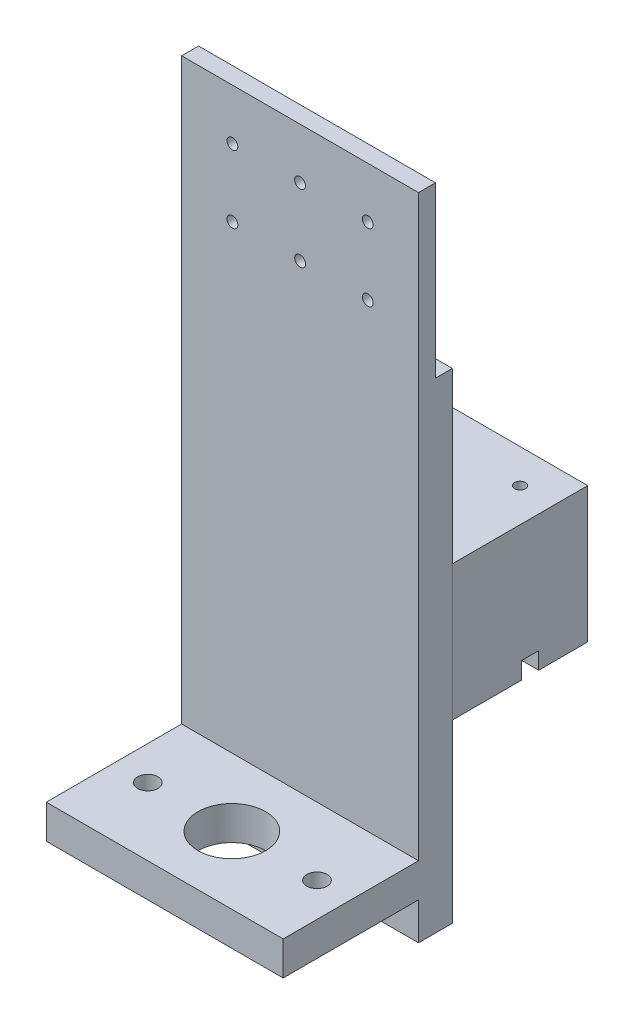
SolidWorks part; units mm, degrees
ref_plane "前视基准面" through (0, 0, 0) normal (0, 0, 1) x (1, 0, 0)
ref_plane "上视基准面" through (0, 0, 0) normal (0, 1, 0) x (1, 0, 0)
ref_plane "右视基准面" through (0, 0, 0) normal (1, 0, 0) x (0, 0, -1)
other "Configuration Table"
sketch "草图1" plane through (0, 0, 0) normal (0, 1, 0) x (1, 0, 0)
  line L1 (-32.1359, 17.2849) -> (37.8641, 17.2849)
  line L2 (-32.1359, 17.2849) -> (-32.1359, -22.7151)
  line L3 (-32.1359, -22.7151) -> (37.8641, -22.7151)
  line L4 (37.8641, 17.2849) -> (37.8641, -22.7151)
  dimension "D1" = 70
  dimension "D2" = 40
extrude "凸台-拉伸1" add sketch "草图1" along normal blind 40
sketch "草图2" plane through (0, 0, 0) normal (0, -1, 0) x (1, 0, 0)
  line L0 (-33.606, 17.7151) -> (40.5423, 17.7151) construction
  line L1 (-32.1359, 22.7151) -> (37.8641, 22.7151) construction
  line L2 (2.8641, 22.7151) -> (2.8641, -17.2849) construction
  line L3 (37.8641, -17.2849) -> (-32.1359, -17.2849) construction
  line L5 (-41.0082, -7.2849) -> (62.2571, -7.2849) construction
  circle A0 centre (-22.1359, 17.7151) radius 1.6
  circle A1 centre (27.8641, 17.7151) radius 1.6
  circle A2 centre (-22.1359, -7.2849) radius 1.6
  circle A3 centre (27.8641, -7.2849) radius 1.6
  dimension "D2" = 25
  dimension "D4" = 25
  dimension "D5" = 3.2
  dimension "D6" = 3.2
  dimension "D1" = 5
  dimension "D3" = 10
extrude "切除-拉伸1" cut sketch "草图2" against normal through all
sketch "草图4" plane through (0, 0, 0) normal (0, -1, 0) x (1, 0, 0)
  line L0 (-32.1359, 22.7151) -> (-32.1359, 32.7151)
  line L1 (-32.1359, 32.7151) -> (37.8641, 32.7151)
  line L2 (37.8641, 32.7151) -> (37.8641, 22.7151)
  line L3 (37.8641, 22.7151) -> (-32.1359, 22.7151)
  dimension "D1" = 10
extrude "凸台-拉伸2" add sketch "草图4" along normal blind 52 and the other way blind 236 separate body contours L3 L0 L1 L2
sketch "草图5" plane through (0, 0, 32.7151) normal (0, 0, 1) x (1, 0, 0)
  line L0 (-38.373, -48) -> (39.7493, -48) construction
  line L1 (-32.1359, -52) -> (37.8641, -52) construction
  line L2 (2.8641, 0) -> (2.8641, -52) construction
  line L3 (-32.1359, 0) -> (37.8641, 0) construction
  circle A0 centre (-18.1359, -48) radius 2.5
  circle A1 centre (23.8641, -48) radius 2.5
  dimension "D2" = 21
  dimension "D3" = 5
  dimension "D1" = 4
extrude "切除-拉伸2" cut sketch "草图5" against normal blind 10
sketch "草图6" plane through (0, 0, 32.7151) normal (0, 0, 1) x (1, 0, 0)
  line L0 (-39.8379, 212) -> (51.2489, 212) construction
  line L1 (-32.1359, 236) -> (37.8641, 236) construction
  line L2 (2.8641, 236) -> (2.8641, 203.179) construction
  circle A0 centre (-18.1359, 212) radius 2.5
  circle A1 centre (23.8641, 212) radius 2.5
  dimension "D2" = 21
  dimension "D3" = 5
  dimension "D1" = 24
extrude "切除-拉伸3" cut sketch "草图6" against normal blind 10
sketch "草图7" plane through (0, 0, 22.7151) normal (0, 0, -1) x (-1, 0, 0)
  line L0 (-37.8641, 236) -> (-37.8641, 246)
  line L1 (-37.8641, 246) -> (32.1359, 246)
  line L2 (32.1359, 246) -> (32.1359, 236)
  line L3 (32.1359, 236) -> (-37.8641, 236)
  dimension "D1" = 10
extrude "凸台-拉伸3" add sketch "草图7" against normal blind 50
sketch "草图8" plane through (0, 236, 0) normal (0, -1, 0) x (1, 0, 0)
  line L0 (-32.1359, 72.7151) -> (37.8641, 32.7151) construction
  line L1 (37.8641, 72.7151) -> (-32.1359, 32.7151) construction
  circle A0 centre (2.8641, 52.7151) radius 12.5
extrude "切除-拉伸4" cut sketch "草图8" against normal blind 10
sketch "草图12" plane through (0, 246, 0) normal (0, 1, 0) x (1, 0, 0)
  line L0 (2.8641, -52.7151) -> (49.57, -52.7151) construction
  line L1 (2.8641, -52.7151) -> (-42.4096, -52.7151) construction
  line L2 (2.8641, -22.7151) -> (2.8641, -78.6614) construction
  line L3 (-32.1359, -22.7151) -> (37.8641, -22.7151) construction
  line L4 (-14.6359, -35.2151) -> (-14.6359, -70.2151) construction
  line L5 (-16.6359, -33.2151) -> (22.3641, -33.2151)
  line L6 (-16.6359, -33.2151) -> (-16.6359, -72.2151)
  line L7 (-16.6359, -72.2151) -> (22.3641, -72.2151)
  line L8 (22.3641, -33.2151) -> (22.3641, -72.2151)
  line L9 (-14.6359, -70.2151) -> (20.3641, -70.2151) construction
  line L10 (20.3641, -35.2151) -> (20.3641, -70.2151) construction
  line L11 (-14.6359, -35.2151) -> (20.3641, -35.2151) construction
  dimension "D1" = 39
  dimension "D2" = 39
  dimension "D3" = 19.5
  dimension "D5" = 19.5
  dimension "D4" = 2
extrude "拉伸-薄壁2" add sketch "草图12" along normal blind 15 thin
sketch "草图14" plane through (0, 261, 0) normal (0, 1, 0) x (1, 0, 0)
  line L0 (-16.6359, -52.7151) -> (22.3641, -52.7151) construction
  line L1 (-16.6359, -33.2151) -> (-16.6359, -72.2151) construction
  line L2 (22.3641, -72.2151) -> (22.3641, -33.2151) construction
  line L3 (2.8641, -33.2151) -> (2.8641, -72.2151) construction
  line L4 (22.3641, -33.2151) -> (-16.6359, -33.2151) construction
  line L5 (-16.6359, -72.2151) -> (22.3641, -72.2151) construction
  circle A0 centre (-12.6359, -37.2151) radius 2
  circle A1 centre (18.3641, -37.2151) radius 2
  circle A2 centre (-12.6359, -68.2151) radius 2
  circle A3 centre (18.3641, -68.2151) radius 2
  dimension "D1" = 15.5
  dimension "D2" = 15.5
extrude "切除-拉伸5" cut sketch "草图14" against normal blind 25
sketch "草图15" plane through (0, 0, 0) normal (0, -1, 0) x (1, 0, 0)
  line L0 (-32.1359, -0.2849) -> (37.8641, -0.2849) construction
  line L1 (-32.1359, -17.2849) -> (-32.1359, 22.7151) construction
  line L2 (37.8641, 22.7151) -> (37.8641, -17.2849) construction
  line L3 (-32.1359, 2.2151) -> (37.8641, 2.2151)
  line L4 (37.8641, 2.2151) -> (37.8641, -2.7849)
  line L5 (37.8641, -2.7849) -> (-32.1359, -2.7849)
  line L6 (-32.1359, -2.7849) -> (-32.1359, 2.2151)
  circle A0 centre (-22.1359, -7.2849) radius 1.6 construction
  dimension "D1" = 7
  dimension "D2" = 5
  dimension "D3" = 2.5
extrude "切除-拉伸6" cut sketch "草图15" against normal blind 5
ref_plane "基准面3" through (0, 97, 0) normal (0, 1, 0) x (1, 0, 0)
ref_plane "基准面4" through (2.8641, 0, 0) normal (-1, 0, 0) x (0, 0, 1)
sketch "草图16" plane through (0, 0, 32.7151) normal (0, 0, 1) x (1, 0, 0)
  line L0 (-39.1209, -41) -> (51.1456, -41) construction
  line L1 (-32.1359, -41) -> (37.8641, -41)
  line L2 (-32.1359, 236) -> (-32.1359, -52) construction
  line L3 (37.8641, 236) -> (37.8641, -52) construction
  line L4 (-32.1359, -41) -> (-32.1359, -31)
  line L5 (-32.1359, -31) -> (37.8641, -31)
  line L6 (37.8641, -31) -> (37.8641, -41)
  circle A0 centre (-18.1359, -48) radius 2.5 construction
  dimension "D1" = 7
  dimension "D2" = 10
extrude "凸台-拉伸4" add sketch "草图16" along normal blind 40
sketch "草图18" plane through (0, -41, 0) normal (0, -1, 0) x (1, 0, 0)
  line L0 (-46.5587, 52.7151) -> (64.0912, 52.7151) construction
  line L1 (-32.1359, 32.7151) -> (37.8641, 32.7151) construction
  line L2 (-32.1359, 72.7151) -> (-32.1359, 32.7151) construction
  line L3 (37.8641, 72.7151) -> (37.8641, 32.7151) construction
  circle A0 centre (-22.1359, 52.7151) radius 3
  circle A1 centre (27.8641, 52.7151) radius 3
  dimension "D2" = 10
  dimension "D3" = 6
  dimension "D4" = 10
  dimension "D1" = 20
extrude "切除-拉伸7" cut sketch "草图18" against normal through all
sketch "草图19" plane through (0, -41, 0) normal (0, -1, 0) x (1, 0, 0)
  circle A0 centre (-22.1359, 52.7151) radius 3
  circle A1 centre (27.8641, 52.7151) radius 3
extrude "凸台-拉伸5" add sketch "草图19" against normal blind 4
sketch "草图24" plane through (0, -41, 0) normal (0, -1, 0) x (1, 0, 0)
  line L0 (-46.9204, 52.7151) -> (52.3293, 52.7151) construction
  line L1 (-32.1359, 32.7151) -> (37.8641, 32.7151) construction
  line L2 (2.8641, 72.7151) -> (2.8641, 32.7151) construction
  line L3 (-32.1359, 72.7151) -> (37.8641, 72.7151) construction
  line L4 (-32.1359, 32.7151) -> (37.8641, 32.7151) construction
  circle A0 centre (2.7045, 52.7151) radius 10
  dimension "D1" = 20
extrude "切除-拉伸9" cut sketch "草图24" against normal up to next (10 mm away)
sketch "草图25" plane through (-32.1359, 0, 0) normal (-1, 0, 0) x (0, 0, 1)
  line L0 (22.7151, 40) -> (22.7151, 90) construction
  line L1 (22.7151, 246) -> (22.7151, -52) construction
  line L2 (22.7151, 90) -> (27.7151, 90)
  line L3 (27.7151, 90) -> (27.7151, 140)
  line L4 (27.7151, 140) -> (32.7151, 140)
  line L5 (32.7151, 236) -> (32.7151, -31) construction
  dimension "D1" = 5
  dimension "D2" = 50
  dimension "D3" = 50
sketch "草图26" plane through (0, 0, 22.7151) normal (0, 0, -1) x (-1, 0, 0)
  line L0 (-54.9443, 105) -> (43.7134, 105) construction
  line L1 (-37.8641, 40) -> (32.1359, 40) construction
  line L2 (-67.2706, 125) -> (56.3914, 125) construction
  line L3 (32.1359, 90) -> (32.1359, 140) construction
  line L4 (-37.8641, 246) -> (-37.8641, -52) construction
  line L5 (-50.5061, 115) -> (45.9338, 115) construction
  circle A0 centre (17.1359, 105) radius 1.6
  circle A1 centre (-2.8641, 105) radius 1.6
  circle A2 centre (-22.8641, 105) radius 1.6
  circle A3 centre (17.1359, 125) radius 1.6
  circle A4 centre (-2.8641, 125) radius 1.6
  circle A5 centre (-22.8641, 125) radius 1.6
  dimension "D3" = 15
  dimension "D4" = 35
  dimension "D5" = 15
  dimension "D1" = 65
  dimension "D2" = 85
  dimension "D6" = 10
extrude "切除-拉伸10" cut sketch "草图26" against normal blind 10
split "分割1" trim tools "草图25" bodies to split 137 resulting bodies 138 139
other "保存实体1"
delete or keep bodies "实体-删除/保留 1" type delete bodies bodies 140
